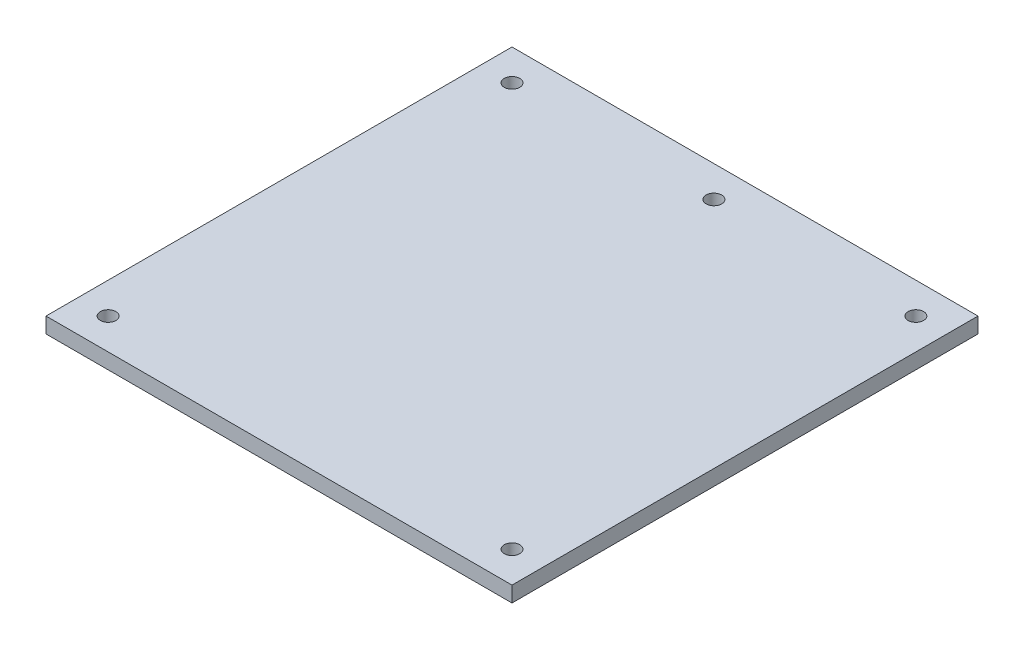
SolidWorks part; units mm, degrees
ref_plane "Plano frontal" through (0, 0, 0) normal (0, 0, 1) x (1, 0, 0)
ref_plane "Plano superior" through (0, 0, 0) normal (0, 1, 0) x (1, 0, 0)
ref_plane "Plano direito" through (0, 0, 0) normal (1, 0, 0) x (0, 0, -1)
sketch "Esboço1" plane through (0, 0, 0) normal (0, 1, 0) x (1, 0, 0)
  line L0 (124.5946, 13.6486) -> (124.5946, -286.3514) construction
  line L1 (-25.4054, -286.3514) -> (274.5946, -286.3514)
  line L2 (-25.4054, -286.3514) -> (-25.4054, 13.6486)
  line L3 (-25.4054, 13.6486) -> (274.5946, 13.6486)
  line L4 (274.5946, -286.3514) -> (274.5946, 13.6486)
  line L5 (-25.4054, -136.3514) -> (274.5946, -136.3514) construction
  circle A0 centre (-5.4054, -6.3514) radius 5
  circle A1 centre (254.5946, -6.3514) radius 5
  circle A2 centre (254.5946, -266.3514) radius 5
  circle A3 centre (-5.4054, -266.3514) radius 5
  circle A4 centre (124.5946, -6.3514) radius 5
  point P18 (0, 0)
  dimension "D3" = 10
  dimension "D4" = 20
  dimension "D5" = 20
  dimension "D6" = 20
  dimension "D1" = 300
  dimension "D2" = 300
extrude "Ressalto-extrusão1" add sketch "Esboço1" along normal blind 10
